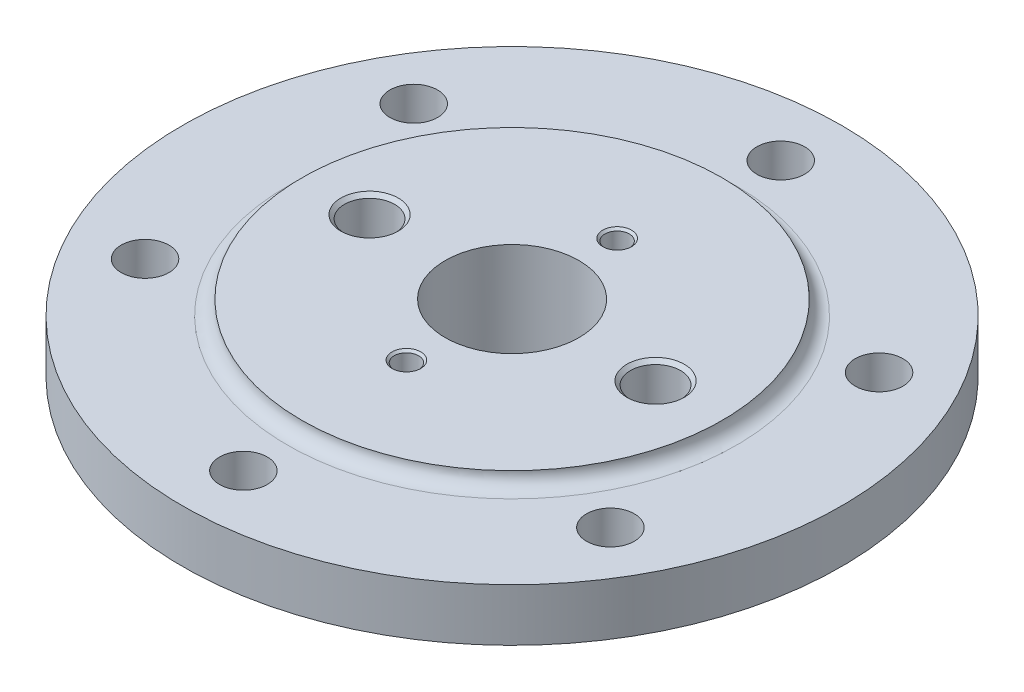
SolidWorks part; units mm, degrees
ref_plane "Front Plane" through (0, 0, 0) normal (0, 0, 1) x (1, 0, 0)
ref_plane "Top Plane" through (0, 0, 0) normal (0, 1, 0) x (1, 0, 0)
ref_plane "Right Plane" through (0, 0, 0) normal (1, 0, 0) x (0, 0, -1)
sketch "Sketch2" plane through (0, 0, 0) normal (0, 0, 1) x (1, 0, 0)
  line L0 (0, 0) -> (0, 95.8135) construction
  line L1 (0, 0) -> (164.456, 0) construction
  line L2 (7, 0) -> (7, 20.8756)
  line L3 (7, 20.8756) -> (28, 33)
  line L4 (28, 33) -> (28, 81)
  line L5 (28, 81) -> (88, 81)
  line L6 (94, 75) -> (138, 75)
  line L7 (138, 75) -> (138, 53)
  line L8 (138, 53) -> (81, 53)
  line L10 (35, 0) -> (7, 0)
  line L11 (81, 53) -> (81, 47)
  line L12 (81, 47) -> (35, 0)
  arc A0 (88, 81) -> (94, 75) centre (94, 81) ccw
  dimension "D1" = 138
  dimension "D2" = 28
  dimension "D3" = 14
  dimension "D4" = 35
  dimension "D5" = 81
  dimension "D6" = 6
  dimension "D7" = 88
  dimension "D8" = 22
  dimension "D9" = 60
  dimension "D10" = 47
  dimension "D11" = 6
  dimension "D12" = 48
revolve "Revolve1" add sketch "Sketch2" angle 360 about L0
sketch "Sketch3" plane through (0, 75, 0) normal (0, 1, 0) x (1, 0, 0)
  line L0 (0, 0) -> (0, 112.5) construction
  line L1 (0, 0) -> (97.4279, 56.25) construction
  line L2 (0, 0) -> (97.4279, -56.25) construction
  line L3 (0, 0) -> (0, -112.5) construction
  line L4 (0, 0) -> (-97.4279, -56.25) construction
  line L5 (0, 0) -> (-97.4279, 56.25) construction
  circle A4 centre (0, 112.5) radius 10
  circle A5 centre (97.4279, 56.25) radius 10
  circle A6 centre (97.4279, -56.25) radius 10
  circle A7 centre (0, -112.5) radius 10
  circle A8 centre (-97.4279, -56.25) radius 10
  circle A9 centre (-97.4279, 56.25) radius 10
  point P13 (-0.2016, 0.2016)
  point P17 (0, 0)
  dimension "D1" = 20
  dimension "D2" = 112.5
  dimension "D3" = 6
sketch "Sketch4" plane through (0, 81, 0) normal (0, 1, 0) x (1, 0, 0)
  line L0 (-60, 0) -> (60, 0) construction
  line L1 (0, 44) -> (0, -44) construction
  point P1 (60, 0)
  point P2 (-60, 0)
  point P7 (0, 0)
  point P10 (0, 44)
  point P11 (0, 0)
  point P13 (0, 44)
  dimension "D1" = 120
  dimension "D2" = 88
hole_wizard "M12 Tapped Hole1" positions "Sketch7" profile "Sketch6" tap size "M12" standard "ISO"
sketch "Sketch7" plane through (0, 81, 0) normal (0, 1, 0) x (1, 0, 0)
  point P0 (0.0355, -44.2777)
sketch "Sketch6" plane through (0.0355, 81, 44.2777) normal (1, 0, 0) x (0, 0, 1)
  line L0 (0, 0) -> (0, 18.0644)
  line L1 (0, 18.0644) -> (5.1, 15)
  line L2 (5.1, 15) -> (5.1, 0.925)
  line L3 (5.1, 0.925) -> (6.025, 0)
  line L5 (6.025, 0) -> (0, 0)
  line L6 (-5.1, 0.925) -> (-6.025, 0) construction
  line L10 (0, 18.0644) -> (-5.1, 15) construction
  line L11 (0, -6.35) -> (0, 107.95) construction
  dimension "Tap Drill Dia." = 10.2
  dimension "Tap Drill Depth" = 15
  dimension "Near C'Sink Dia." = 12.05
  dimension "Near C'Sink Angle" = 90
  dimension "Drill Angle" = 118
cosmetic thread "Hole Thread1" parameters "D1"=12, "D2"=12
hole_wizard "M12 Tapped Hole3" positions "Sketch4" profile "Sketch8" tap size "M12" standard "ISO"
sketch "Sketch8" plane through (0, 81, -44) normal (1, 0, 0) x (0, 0, 1)
  line L0 (0, 0) -> (0, 18.0644)
  line L1 (0, 18.0644) -> (5.1, 15)
  line L2 (5.1, 15) -> (5.1, 0.925)
  line L3 (5.1, 0.925) -> (6.025, 0)
  line L5 (6.025, 0) -> (0, 0)
  line L6 (-5.1, 0.925) -> (-6.025, 0) construction
  line L10 (0, 18.0644) -> (-5.1, 15) construction
  line L11 (0, -6.35) -> (0, 107.95) construction
  dimension "Tap Drill Dia." = 10.2
  dimension "Tap Drill Depth" = 15
  dimension "Near C'Sink Dia." = 12.05
  dimension "Near C'Sink Angle" = 90
  dimension "Drill Angle" = 118
cosmetic thread "Hole Thread2" parameters "D1"=12, "D2"=12
sketch "Sketch10" plane through (0, 81, 0) normal (0, 1, 0) x (1, 0, 0)
  line L0 (-60, 0) -> (60, 0) construction
  point P6 (0, 0)
  point P9 (-60.4802, 0.8064)
  point P11 (59.6738, 0.4032)
  dimension "D1" = 120
hole_wizard "M24 Tapped Hole2" positions "Sketch10" profile "Sketch11" tap size "M24" standard "ISO"
sketch "Sketch11" plane through (59.6738, 81, -0.4032) normal (1, 0, 0) x (0, 0, 1)
  line L0 (0, 0) -> (0, 39.309)
  line L1 (0, 39.309) -> (10.5, 33)
  line L2 (10.5, 33) -> (10.5, 1.525)
  line L3 (10.5, 1.525) -> (12.025, 0)
  line L5 (12.025, 0) -> (0, 0)
  line L6 (-10.5, 1.525) -> (-12.025, 0) construction
  line L10 (0, 39.309) -> (-10.5, 33) construction
  line L11 (0, -6.35) -> (0, 107.95) construction
  dimension "Tap Drill Dia." = 21
  dimension "Tap Drill Depth" = 33
  dimension "Near C'Sink Dia." = 24.05
  dimension "Near C'Sink Angle" = 90
  dimension "Drill Angle" = 118
cosmetic thread "Hole Thread4" parameters "D1"=24, "D2"=24
cosmetic thread "Hole Thread5" parameters "D1"=24, "D2"=24
extrude "Cut-Extrude1" cut sketch "Sketch3" against normal up to body
